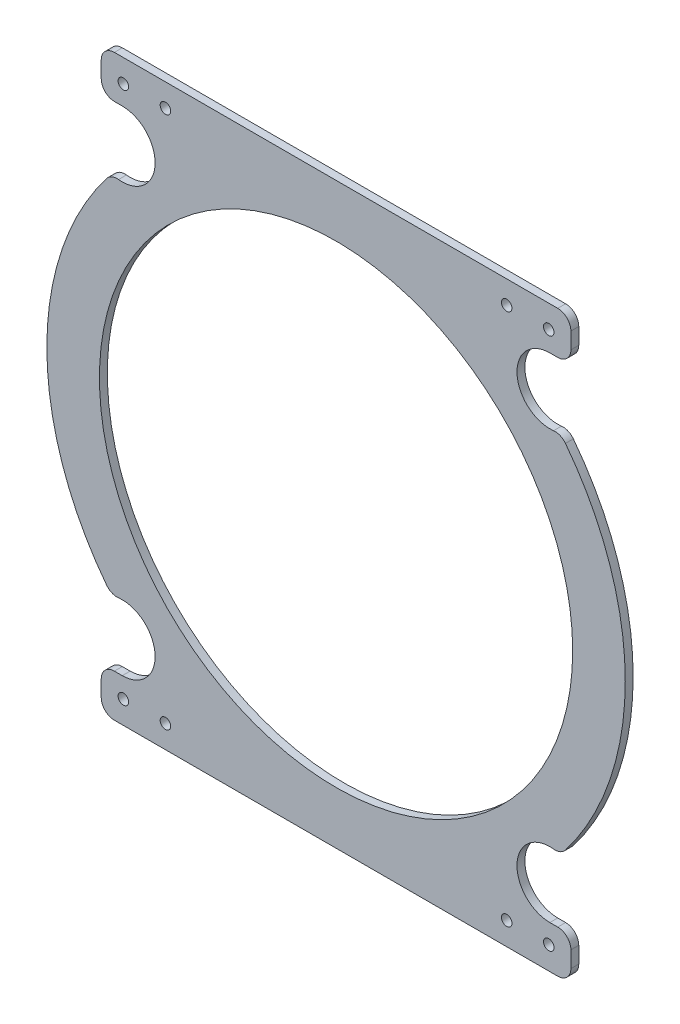
SolidWorks part; units mm, degrees
material "Karbonfiber"
ref_plane "Ön Düzlem" through (0, 0, 0) normal (0, 0, 1) x (1, 0, 0)
ref_plane "Üst Düzlem" through (0, 0, 0) normal (0, 1, 0) x (1, 0, 0)
ref_plane "Sağ Düzlem" through (0, 0, 0) normal (1, 0, 0) x (0, 0, -1)
sketch "Çizim1" plane through (0, 0, 0) normal (0, 0, 1) x (1, 0, 0)
  line L0 (0, 0) -> (0, 110) construction
  line L1 (0, 0) -> (110, 0) construction
  line L2 (0, 0) -> (-81.3173, 81.3173) construction
  line L3 (0, 0) -> (81.3173, 81.3173) construction
  line L4 (0, 0) -> (-81.3173, -81.3173) construction
  line L12 (0, 0) -> (81.3173, -81.3173) construction
  line L13 (-81.3173, 93.8173) -> (-89.3173, 93.8173)
  line L14 (-89.3173, 93.8173) -> (-89.3173, 110)
  line L15 (-89.3173, 110) -> (89.3173, 110)
  line L16 (89.3173, 110) -> (89.3173, 93.8173)
  line L17 (89.3173, 93.8173) -> (81.3173, 93.8173)
  line L18 (89.3173, -93.8173) -> (81.3173, -93.8173)
  line L19 (89.3173, -110) -> (89.3173, -93.8173)
  line L20 (-89.3173, -110) -> (89.3173, -110)
  line L21 (-81.3173, -93.8173) -> (-89.3173, -93.8173)
  line L22 (-89.3173, -93.8173) -> (-89.3173, -110)
  arc A49 (-85.2908, 69.4657) -> (-85.2908, -69.4657) centre (0, 0) ccw
  circle A51 centre (0, 0) radius 90
  circle A53 centre (0, 0) radius 115 construction
  arc A55 (-85.2908, 69.4657) -> (-81.3173, 93.8173) centre (-81.3173, 81.3173) ccw construction
  arc A56 (81.3173, 93.8173) -> (85.2908, 69.4657) centre (81.3173, 81.3173) ccw construction
  circle A57 centre (81.3173, -81.3173) radius 12.5 construction
  circle A58 centre (-81.3173, -81.3173) radius 12.5 construction
  arc A60 (-85.2908, 69.4657) -> (-81.3173, 93.8173) centre (-81.3173, 81.3173) ccw
  arc A62 (81.3173, 93.8173) -> (85.2908, 69.4657) centre (81.3173, 81.3173) ccw
  arc A64 (81.3173, -93.8173) -> (85.2908, -69.4657) centre (81.3173, -81.3173) cw
  circle A66 centre (64.9, 101.3173) radius 2
  circle A67 centre (80.9, 101.3173) radius 2
  circle A68 centre (-80.9, 101.3173) radius 2
  circle A69 centre (-64.9, 101.3173) radius 2
  circle A70 centre (0, 0) radius 50 construction
  circle A71 centre (64.9, -101.3173) radius 2
  circle A72 centre (80.9, -101.3173) radius 2
  circle A73 centre (-64.9, -101.3173) radius 2
  circle A74 centre (-80.9, -101.3173) radius 2
  arc A75 (-85.2908, -69.4657) -> (-81.3173, -93.8173) centre (-81.3173, -81.3173) cw
  arc A76 (69.4657, 85.2908) -> (-69.4657, 85.2908) centre (0, 0) ccw construction
  arc A77 (85.2908, -69.4657) -> (85.2908, 69.4657) centre (0, 0) ccw
  arc A78 (-69.4657, -85.2908) -> (69.4657, -85.2908) centre (0, 0) ccw construction
  dimension "D1" = 220
  dimension "D2" = 180
  dimension "D3" = 115
  dimension "D7" = 230
  dimension "D9" = 100
  dimension "D10" = 8
  dimension "D4" = 115
  dimension "D11" = 8
  dimension "D8" = 25
extrude "Yükseklik-Ekstrüzyon1" add sketch "Çizim1" along normal blind 3 contours A64 A77 A62 L17 L16 L15 L14 L13 A60 A49 A75 L21 L22 L20 L19 L18 A74 A72 A51 A66 A67 A68 A69 A71 A73
fillet "Fillet1" radius 5 12 edges at (-85.2908, -69.4657, 1.5) (-89.3173, -93.8173, 1.5) (-89.3173, -110, 1.5) (89.3173, -110, 1.5) (89.3173, -93.8173, 1.5) (85.2908, -69.4657, 1.5) (85.2908, 69.4657, 1.5) (89.3173, 93.8173, 1.5) (89.3173, 110, 1.5) (-89.3173, 110, 1.5) (-89.3173, 93.8173, 1.5) (-85.2908, 69.4657, 1.5)
